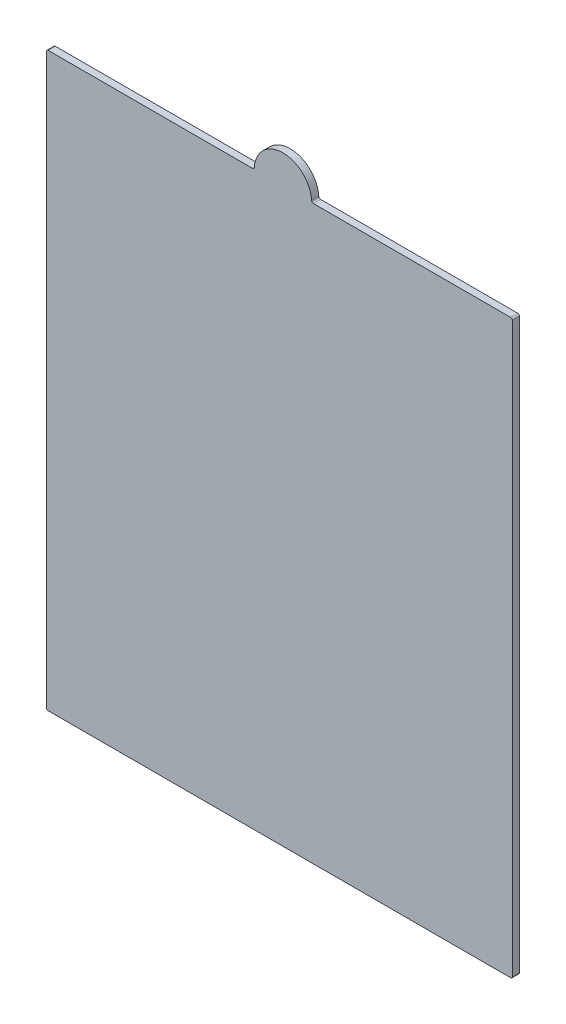
SolidWorks part; units mm, degrees
material "Acrylic (Medium-high impact)"
ref_plane "Front Plane" through (0, 0, 0) normal (0, 0, 1) x (1, 0, 0)
ref_plane "Top Plane" through (0, 0, 0) normal (0, 1, 0) x (1, 0, 0)
ref_plane "Right Plane" through (0, 0, 0) normal (1, 0, 0) x (0, 0, -1)
sketch "Sketch1" plane through (0, 0, 0) normal (0, 0, 1) x (1, 0, 0)
  line L1 (0, 0) -> (206.253, 0)
  line L2 (0, 0) -> (0, 253.103)
  line L3 (0, 253.103) -> (206.253, 253.103)
  line L4 (206.253, 0) -> (206.253, 253.103)
  dimension "D1" = 253.103
  dimension "D2" = 206.253
extrude "Boss-Extrude1" add sketch "Sketch1" along normal blind 3.175
sketch "Sketch3" plane through (0, 0, 0) normal (0, 0, 1) x (1, 0, 0)
  line L0 (206.253, 253.103) -> (0, 253.103) construction
  line L1 (92.0039, 253.103) -> (117.4039, 253.103)
  arc A0 (117.4039, 253.103) -> (92.0039, 253.103) centre (104.7039, 253.103) ccw
  dimension "D1" = 25.4
extrude "Boss-Extrude3" add sketch "Sketch3" along normal blind 3.175
fillet "Fillet1" radius 0.7937 6 edges at (0, 0, 1.5875) (206.253, 0, 1.5875) (206.253, 253.103, 1.5875) (0, 253.103, 1.5875) (92.0039, 253.103, 1.5875) (117.4039, 253.103, 1.5875)
